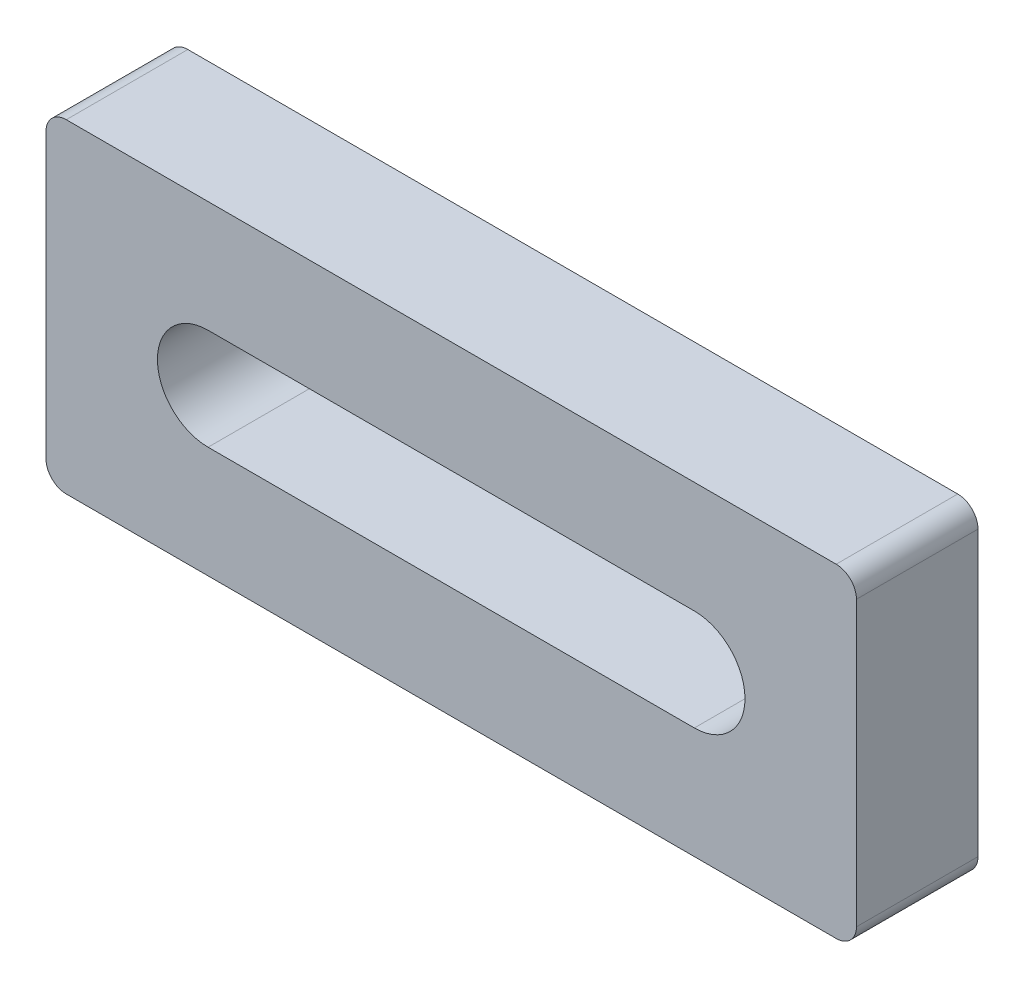
SolidWorks part; units mm, degrees
ref_plane "Plane1" through (0, 0, 0) normal (0, 0, 1) x (1, 0, 0)
ref_plane "Plane2" through (0, 0, 0) normal (0, 1, 0) x (1, 0, 0)
ref_plane "Plane3" through (0, 0, 0) normal (1, 0, 0) x (0, 0, -1)
sketch "Sketch1" plane through (0, 0, 0) normal (0, 0, 1) x (1, 0, 0)
  line L0 (-174.625, 11.1125) -> (-98.425, 11.1125)
  line L1 (-76.2, -6.35) -> (-196.85, -6.35)
  line L2 (-73.025, -3.175) -> (-73.025, 41.275)
  line L3 (-76.2, 44.45) -> (-196.85, 44.45)
  line L4 (-200.025, -3.175) -> (-200.025, 41.275)
  line L5 (-174.625, 26.9875) -> (-98.425, 26.9875)
  arc A0 (-200.025, -3.175) -> (-196.85, -6.35) centre (-196.85, -3.175) ccw
  arc A1 (-200.025, 41.275) -> (-196.85, 44.45) centre (-196.85, 41.275) cw
  arc A2 (-76.2, -6.35) -> (-73.025, -3.175) centre (-76.2, -3.175) ccw
  arc A3 (-76.2, 44.45) -> (-73.025, 41.275) centre (-76.2, 41.275) cw
  arc A6 (-174.625, 26.9875) -> (-174.625, 11.1125) centre (-174.625, 19.05) ccw
  arc A7 (-98.425, 11.1125) -> (-98.425, 26.9875) centre (-98.425, 19.05) ccw
  dimension "D1" = 3.175
  dimension "D2" = 3.175
  dimension "D5" = 25.4
  dimension "D3" = 127
  dimension "D4" = 25.4
  dimension "D6" = 50.8
  dimension "D7" = 15.875
extrude "Base-Extrude" add sketch "Sketch1" along normal blind 19.05
